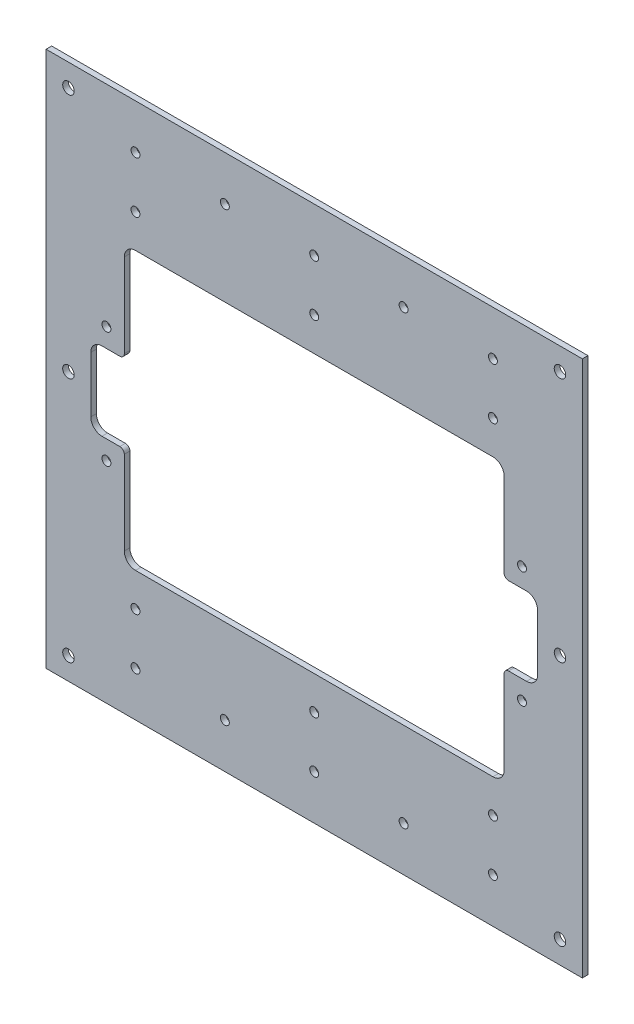
SolidWorks part; units mm, degrees
ref_plane "Front Plane" through (0, 0, 0) normal (0, 0, 1) x (1, 0, 0)
ref_plane "Top Plane" through (0, 0, 0) normal (0, 1, 0) x (1, 0, 0)
ref_plane "Right Plane" through (0, 0, 0) normal (1, 0, 0) x (0, 0, -1)
sketch "Sketch1" plane through (0, 0, 0) normal (0, 0, 1) x (1, 0, 0)
  line L0 (-152.4, 127) -> (-76.2, 127) construction
  line L1 (-152.4, 152.4) -> (152.4, 152.4)
  line L2 (-152.4, 152.4) -> (-152.4, -152.4)
  line L3 (-152.4, -152.4) -> (152.4, -152.4)
  line L4 (152.4, 152.4) -> (152.4, -152.4)
  line L5 (-76.2, 127) -> (-25.4, 127) construction
  line L6 (-25.4, 127) -> (25.4, 127) construction
  line L7 (25.4, 127) -> (76.2, 127) construction
  line L8 (76.2, 127) -> (152.4, 127) construction
  line L9 (-152.4, 0) -> (152.4, 0) construction
  line L10 (0, 152.4) -> (0, -152.4) construction
  line L11 (-118.11, 152.4) -> (-118.11, -152.4) construction
  line L12 (-152.4, -127) -> (152.4, -127) construction
  line L13 (127, 152.4) -> (127, -152.4) construction
  line L14 (-50.8, 152.4) -> (-50.8, -152.4) construction
  line L15 (50.8, 152.4) -> (50.8, -152.4) construction
  line L16 (-101.6, 152.4) -> (-101.6, -152.4) construction
  line L17 (-95.25, 66.04) -> (-57.15, 66.04) construction
  line L18 (-95.25, 66.04) -> (-95.25, -66.04) construction
  line L19 (-95.25, -66.04) -> (-57.15, -66.04) construction
  line L20 (-57.15, 66.04) -> (-57.15, -66.04) construction
  line L21 (-44.45, 66.04) -> (-6.35, 66.04) construction
  line L22 (-44.45, 66.04) -> (-44.45, -66.04) construction
  line L23 (-44.45, -66.04) -> (-6.35, -66.04) construction
  line L24 (-6.35, 66.04) -> (-6.35, -66.04) construction
  line L25 (6.35, 66.04) -> (44.45, 66.04) construction
  line L26 (6.35, 66.04) -> (6.35, -66.04) construction
  line L27 (6.35, -66.04) -> (44.45, -66.04) construction
  line L28 (44.45, 66.04) -> (44.45, -66.04) construction
  line L29 (57.15, 66.04) -> (95.25, 66.04) construction
  line L30 (57.15, 66.04) -> (57.15, -66.04) construction
  line L31 (57.15, -66.04) -> (95.25, -66.04) construction
  line L32 (95.25, 66.04) -> (95.25, -66.04) construction
  line L33 (101.6, 152.4) -> (101.6, -152.4) construction
  line L34 (-152.4, 120.65) -> (152.4, 120.65) construction
  line L35 (-101.6, 39.7057) -> (-95.25, 39.7057) construction
  line L36 (-57.15, 39.7057) -> (-50.8, 39.7057) construction
  line L37 (-76.2, 66.04) -> (-76.2, 0) construction
  line L38 (-76.2, 0) -> (-76.2, -66.04) construction
  line L39 (-152.4, 72.39) -> (152.4, 72.39) construction
  line L40 (-152.4, -72.39) -> (152.4, -72.39) construction
  line L41 (-76.2, 66.04) -> (-76.2, 72.39) construction
  line L42 (-95.25, -66.04) -> (-95.25, -72.39) construction
  line L43 (95.25, 39.7057) -> (101.6, 39.7057) construction
  line L44 (-95.25, 111.76) -> (-57.15, 111.76) construction
  line L45 (-57.15, 111.76) -> (-57.15, 118.4779) construction
  line L46 (-94.0266, 120.65) -> (-78.1749, 130.2582) construction
  line L47 (-95.25, 111.76) -> (-95.25, 118.4779) construction
  line L48 (-58.3734, 120.65) -> (-74.2251, 130.2582) construction
  line L49 (-107.3169, 130.81) -> (-83.1894, 130.81) construction
  line L50 (-6.35, 111.76) -> (-6.35, 118.4779) construction
  line L51 (-7.5734, 120.65) -> (-23.4251, 130.2582) construction
  line L52 (-43.2266, 120.65) -> (-27.3749, 130.2582) construction
  line L53 (-44.45, 111.76) -> (-44.45, 118.4779) construction
  line L54 (-6.35, 111.76) -> (-44.45, 111.76) construction
  line L55 (44.45, 111.76) -> (44.45, 118.4779) construction
  line L56 (43.2266, 120.65) -> (27.3749, 130.2582) construction
  line L57 (7.5734, 120.65) -> (23.4251, 130.2582) construction
  line L58 (6.35, 111.76) -> (6.35, 118.4779) construction
  line L59 (6.35, 111.76) -> (44.45, 111.76) construction
  line L60 (95.25, 111.76) -> (57.15, 111.76) construction
  line L61 (95.25, 111.76) -> (95.25, 118.4779) construction
  line L62 (94.0266, 120.65) -> (78.1749, 130.2582) construction
  line L63 (58.3734, 120.65) -> (74.2251, 130.2582) construction
  line L64 (57.15, 111.76) -> (57.15, 118.4779) construction
  line L65 (-95.25, -111.76) -> (-95.25, -118.4779) construction
  line L66 (-94.0266, -120.65) -> (-78.1749, -130.2582) construction
  line L67 (-58.3734, -120.65) -> (-74.2251, -130.2582) construction
  line L68 (-95.25, -111.76) -> (-57.15, -111.76) construction
  line L69 (-57.15, -111.76) -> (-57.15, -118.4779) construction
  line L70 (-44.45, -111.76) -> (-44.45, -118.4779) construction
  line L71 (-43.2266, -120.65) -> (-27.3749, -130.2582) construction
  line L72 (-6.35, -111.76) -> (-44.45, -111.76) construction
  line L73 (-7.5734, -120.65) -> (-23.4251, -130.2582) construction
  line L74 (-6.35, -111.76) -> (-6.35, -118.4779) construction
  line L75 (6.35, -111.76) -> (6.35, -118.4779) construction
  line L76 (7.5734, -120.65) -> (23.4251, -130.2582) construction
  line L77 (43.2266, -120.65) -> (27.3749, -130.2582) construction
  line L78 (6.35, -111.76) -> (44.45, -111.76) construction
  line L79 (44.45, -111.76) -> (44.45, -118.4779) construction
  line L80 (57.15, -111.76) -> (57.15, -118.4779) construction
  line L81 (58.3734, -120.65) -> (74.2251, -130.2582) construction
  line L82 (94.0266, -120.65) -> (78.1749, -130.2582) construction
  line L83 (95.25, -111.76) -> (57.15, -111.76) construction
  line L84 (95.25, -111.76) -> (95.25, -118.4779) construction
  line L85 (-152.4, 97.79) -> (152.4, 97.79) construction
  line L86 (-50.8, 39.7057) -> (-44.45, 39.7057) construction
  line L87 (-127, 152.4) -> (-127, -152.4) construction
  line L89 (-95.25, 101.6) -> (-92.3192, 101.6) construction
  line L90 (-95.25, 101.6) -> (-95.25, -101.6) construction
  line L96 (-90.8538, 101.6) -> (-90.8538, 68.58) construction
  line L97 (-89.3885, 101.6) -> (-89.3885, 68.58) construction
  line L98 (-92.3192, 101.6) -> (-92.3192, 68.58) construction
  line L99 (-83.5269, 101.6) -> (-83.5269, 68.58) construction
  line L100 (-86.4577, 101.6) -> (-86.4577, 68.58) construction
  line L101 (-89.3885, 101.6) -> (-86.4577, 101.6) construction
  line L102 (-77.6654, 101.6) -> (-77.6654, 68.58) construction
  line L103 (-80.5962, 101.6) -> (-80.5962, 68.58) construction
  line L104 (-83.5269, 101.6) -> (-80.5962, 101.6) construction
  line L105 (-71.8038, 101.6) -> (-71.8038, 68.58) construction
  line L106 (-74.7346, 101.6) -> (-74.7346, 68.58) construction
  line L107 (-77.6654, 101.6) -> (-74.7346, 101.6) construction
  line L108 (-65.9423, 101.6) -> (-65.9423, 68.58) construction
  line L109 (-68.8731, 101.6) -> (-68.8731, 68.58) construction
  line L110 (-71.8038, 101.6) -> (-68.8731, 101.6) construction
  line L111 (-60.0808, 101.6) -> (-60.0808, 68.58) construction
  line L112 (-63.0115, 101.6) -> (-63.0115, 68.58) construction
  line L113 (-65.9423, 101.6) -> (-63.0115, 101.6) construction
  line L114 (-57.15, -101.6) -> (-57.15, 101.6) construction
  line L115 (-60.0808, 101.6) -> (-57.15, 101.6) construction
  line L116 (-92.3192, 68.58) -> (-89.3885, 68.58) construction
  line L117 (-60.0808, -101.6) -> (-57.15, -101.6) construction
  line L118 (-60.0808, -101.6) -> (-60.0808, -68.58) construction
  line L119 (-63.0115, -101.6) -> (-63.0115, -68.58) construction
  line L120 (-65.9423, -101.6) -> (-65.9423, -68.58) construction
  line L121 (-65.9423, -101.6) -> (-63.0115, -101.6) construction
  line L122 (-68.8731, -101.6) -> (-68.8731, -68.58) construction
  line L123 (-71.8038, -101.6) -> (-68.8731, -101.6) construction
  line L124 (-71.8038, -101.6) -> (-71.8038, -68.58) construction
  line L125 (-74.7346, -101.6) -> (-74.7346, -68.58) construction
  line L126 (-77.6654, -101.6) -> (-74.7346, -101.6) construction
  line L127 (-77.6654, -101.6) -> (-77.6654, -68.58) construction
  line L128 (-80.5962, -101.6) -> (-80.5962, -68.58) construction
  line L129 (-83.5269, -101.6) -> (-80.5962, -101.6) construction
  line L130 (-83.5269, -101.6) -> (-83.5269, -68.58) construction
  line L131 (-86.4577, -101.6) -> (-86.4577, -68.58) construction
  line L132 (-89.3885, -101.6) -> (-86.4577, -101.6) construction
  line L133 (-89.3885, -101.6) -> (-89.3885, -68.58) construction
  line L134 (-92.3192, -101.6) -> (-92.3192, -68.58) construction
  line L135 (-95.25, -101.6) -> (-92.3192, -101.6) construction
  line L136 (-9.2808, 68.58) -> (-12.2115, 68.58) construction
  line L137 (6.35, 66.04) -> (44.45, 66.04) construction
  line L138 (-6.35, -66.04) -> (-6.35, -72.39) construction
  line L139 (-25.4, 66.04) -> (-25.4, 72.39) construction
  line L140 (-25.4, 0) -> (-25.4, -66.04) construction
  line L141 (-25.4, 66.04) -> (-25.4, 0) construction
  line L142 (-44.45, 66.04) -> (-44.45, -66.04) construction
  line L143 (-6.35, -66.04) -> (-44.45, -66.04) construction
  line L144 (-6.35, 66.04) -> (-6.35, -66.04) construction
  line L145 (-6.35, 66.04) -> (-44.45, 66.04) construction
  line L146 (-6.35, -101.6) -> (-9.2808, -101.6) construction
  line L147 (-9.2808, -101.6) -> (-9.2808, -68.58) construction
  line L148 (-12.2115, -101.6) -> (-12.2115, -68.58) construction
  line L149 (-12.2115, -101.6) -> (-15.1423, -101.6) construction
  line L150 (-15.1423, -101.6) -> (-15.1423, -68.58) construction
  line L151 (-18.0731, -101.6) -> (-18.0731, -68.58) construction
  line L152 (-18.0731, -101.6) -> (-21.0038, -101.6) construction
  line L153 (-21.0038, -101.6) -> (-21.0038, -68.58) construction
  line L154 (-23.9346, -101.6) -> (-23.9346, -68.58) construction
  line L155 (-23.9346, -101.6) -> (-26.8654, -101.6) construction
  line L156 (-26.8654, -101.6) -> (-26.8654, -68.58) construction
  line L157 (-29.7962, -101.6) -> (-29.7962, -68.58) construction
  line L158 (-29.7962, -101.6) -> (-32.7269, -101.6) construction
  line L159 (-32.7269, -101.6) -> (-32.7269, -68.58) construction
  line L160 (-35.6577, -101.6) -> (-38.5885, -101.6) construction
  line L161 (-35.6577, -101.6) -> (-35.6577, -68.58) construction
  line L162 (-38.5885, -101.6) -> (-38.5885, -68.58) construction
  line L163 (-41.5192, -101.6) -> (-41.5192, -68.58) construction
  line L164 (-41.5192, -101.6) -> (-44.45, -101.6) construction
  line L165 (-41.5192, 101.6) -> (-44.45, 101.6) construction
  line L166 (-44.45, -101.6) -> (-44.45, 101.6) construction
  line L167 (-35.6577, 101.6) -> (-38.5885, 101.6) construction
  line L168 (-38.5885, 101.6) -> (-38.5885, 68.58) construction
  line L169 (-41.5192, 101.6) -> (-41.5192, 68.58) construction
  line L170 (-29.7962, 101.6) -> (-32.7269, 101.6) construction
  line L171 (-32.7269, 101.6) -> (-32.7269, 68.58) construction
  line L172 (-35.6577, 101.6) -> (-35.6577, 68.58) construction
  line L173 (-23.9346, 101.6) -> (-26.8654, 101.6) construction
  line L174 (-26.8654, 101.6) -> (-26.8654, 68.58) construction
  line L175 (-29.7962, 101.6) -> (-29.7962, 68.58) construction
  line L176 (-18.0731, 101.6) -> (-21.0038, 101.6) construction
  line L177 (-21.0038, 101.6) -> (-21.0038, 68.58) construction
  line L178 (-23.9346, 101.6) -> (-23.9346, 68.58) construction
  line L179 (-12.2115, 101.6) -> (-15.1423, 101.6) construction
  line L180 (-15.1423, 101.6) -> (-15.1423, 68.58) construction
  line L181 (-18.0731, 101.6) -> (-18.0731, 68.58) construction
  line L182 (-9.2808, 101.6) -> (-9.2808, 68.58) construction
  line L183 (-12.2115, 101.6) -> (-12.2115, 68.58) construction
  line L184 (-6.35, 101.6) -> (-6.35, -101.6) construction
  line L185 (-6.35, 101.6) -> (-9.2808, 101.6) construction
  line L186 (6.35, 66.04) -> (6.35, -66.04) construction
  line L187 (6.35, -66.04) -> (44.45, -66.04) construction
  line L188 (44.45, 66.04) -> (44.45, -66.04) construction
  line L189 (25.4, 66.04) -> (25.4, 0) construction
  line L190 (25.4, 0) -> (25.4, -66.04) construction
  line L191 (25.4, 66.04) -> (25.4, 72.39) construction
  line L192 (6.35, -66.04) -> (6.35, -72.39) construction
  line L193 (9.2808, 68.58) -> (12.2115, 68.58) construction
  line L194 (6.35, 66.04) -> (6.35, -66.04) construction
  line L195 (44.45, -66.04) -> (6.35, -66.04) construction
  line L196 (44.45, 66.04) -> (44.45, -66.04) construction
  line L197 (44.45, 66.04) -> (6.35, 66.04) construction
  line L198 (6.35, 101.6) -> (9.2808, 101.6) construction
  line L199 (6.35, 101.6) -> (6.35, -101.6) construction
  line L200 (12.2115, 101.6) -> (12.2115, 68.58) construction
  line L201 (9.2808, 101.6) -> (9.2808, 68.58) construction
  line L202 (18.0731, 101.6) -> (18.0731, 68.58) construction
  line L203 (15.1423, 101.6) -> (15.1423, 68.58) construction
  line L204 (12.2115, 101.6) -> (15.1423, 101.6) construction
  line L205 (23.9346, 101.6) -> (23.9346, 68.58) construction
  line L206 (21.0038, 101.6) -> (21.0038, 68.58) construction
  line L207 (18.0731, 101.6) -> (21.0038, 101.6) construction
  line L208 (29.7962, 101.6) -> (29.7962, 68.58) construction
  line L209 (26.8654, 101.6) -> (26.8654, 68.58) construction
  line L210 (23.9346, 101.6) -> (26.8654, 101.6) construction
  line L211 (35.6577, 101.6) -> (35.6577, 68.58) construction
  line L212 (32.7269, 101.6) -> (32.7269, 68.58) construction
  line L213 (29.7962, 101.6) -> (32.7269, 101.6) construction
  line L214 (41.5192, 101.6) -> (41.5192, 68.58) construction
  line L215 (38.5885, 101.6) -> (38.5885, 68.58) construction
  line L216 (35.6577, 101.6) -> (38.5885, 101.6) construction
  line L217 (44.45, -101.6) -> (44.45, 101.6) construction
  line L218 (41.5192, 101.6) -> (44.45, 101.6) construction
  line L219 (41.5192, -101.6) -> (44.45, -101.6) construction
  line L220 (41.5192, -101.6) -> (41.5192, -68.58) construction
  line L221 (38.5885, -101.6) -> (38.5885, -68.58) construction
  line L222 (35.6577, -101.6) -> (35.6577, -68.58) construction
  line L223 (35.6577, -101.6) -> (38.5885, -101.6) construction
  line L224 (32.7269, -101.6) -> (32.7269, -68.58) construction
  line L225 (29.7962, -101.6) -> (32.7269, -101.6) construction
  line L226 (29.7962, -101.6) -> (29.7962, -68.58) construction
  line L227 (26.8654, -101.6) -> (26.8654, -68.58) construction
  line L228 (23.9346, -101.6) -> (26.8654, -101.6) construction
  line L229 (23.9346, -101.6) -> (23.9346, -68.58) construction
  line L230 (21.0038, -101.6) -> (21.0038, -68.58) construction
  line L231 (18.0731, -101.6) -> (21.0038, -101.6) construction
  line L232 (18.0731, -101.6) -> (18.0731, -68.58) construction
  line L233 (15.1423, -101.6) -> (15.1423, -68.58) construction
  line L234 (12.2115, -101.6) -> (15.1423, -101.6) construction
  line L235 (12.2115, -101.6) -> (12.2115, -68.58) construction
  line L236 (9.2808, -101.6) -> (9.2808, -68.58) construction
  line L237 (6.35, -101.6) -> (9.2808, -101.6) construction
  line L238 (57.15, 66.04) -> (95.25, 66.04) construction
  line L239 (57.15, 66.04) -> (57.15, -66.04) construction
  line L240 (57.15, -66.04) -> (95.25, -66.04) construction
  line L241 (95.25, 66.04) -> (95.25, -66.04) construction
  line L242 (92.3192, 68.58) -> (89.3885, 68.58) construction
  line L243 (95.25, -66.04) -> (95.25, -72.39) construction
  line L244 (76.2, 66.04) -> (76.2, 72.39) construction
  line L245 (76.2, 0) -> (76.2, -66.04) construction
  line L246 (76.2, 66.04) -> (76.2, 0) construction
  line L247 (57.15, 66.04) -> (57.15, -66.04) construction
  line L248 (95.25, -66.04) -> (57.15, -66.04) construction
  line L249 (95.25, 66.04) -> (95.25, -66.04) construction
  line L250 (95.25, 66.04) -> (57.15, 66.04) construction
  line L251 (57.15, 66.04) -> (57.15, -66.04) construction
  line L252 (95.25, -66.04) -> (57.15, -66.04) construction
  line L253 (95.25, 66.04) -> (95.25, -66.04) construction
  line L254 (95.25, 66.04) -> (57.15, 66.04) construction
  line L255 (95.25, -101.6) -> (92.3192, -101.6) construction
  line L256 (92.3192, -101.6) -> (92.3192, -68.58) construction
  line L257 (89.3885, -101.6) -> (89.3885, -68.58) construction
  line L258 (89.3885, -101.6) -> (86.4577, -101.6) construction
  line L259 (86.4577, -101.6) -> (86.4577, -68.58) construction
  line L260 (83.5269, -101.6) -> (83.5269, -68.58) construction
  line L261 (83.5269, -101.6) -> (80.5962, -101.6) construction
  line L262 (80.5962, -101.6) -> (80.5962, -68.58) construction
  line L263 (77.6654, -101.6) -> (77.6654, -68.58) construction
  line L264 (77.6654, -101.6) -> (74.7346, -101.6) construction
  line L265 (74.7346, -101.6) -> (74.7346, -68.58) construction
  line L266 (71.8038, -101.6) -> (71.8038, -68.58) construction
  line L267 (71.8038, -101.6) -> (68.8731, -101.6) construction
  line L268 (68.8731, -101.6) -> (68.8731, -68.58) construction
  line L269 (65.9423, -101.6) -> (63.0115, -101.6) construction
  line L270 (65.9423, -101.6) -> (65.9423, -68.58) construction
  line L271 (63.0115, -101.6) -> (63.0115, -68.58) construction
  line L272 (60.0808, -101.6) -> (60.0808, -68.58) construction
  line L273 (60.0808, -101.6) -> (57.15, -101.6) construction
  line L274 (60.0808, 101.6) -> (57.15, 101.6) construction
  line L275 (57.15, -101.6) -> (57.15, 101.6) construction
  line L276 (65.9423, 101.6) -> (63.0115, 101.6) construction
  line L277 (63.0115, 101.6) -> (63.0115, 68.58) construction
  line L278 (60.0808, 101.6) -> (60.0808, 68.58) construction
  line L279 (71.8038, 101.6) -> (68.8731, 101.6) construction
  line L280 (68.8731, 101.6) -> (68.8731, 68.58) construction
  line L281 (65.9423, 101.6) -> (65.9423, 68.58) construction
  line L282 (77.6654, 101.6) -> (74.7346, 101.6) construction
  line L283 (74.7346, 101.6) -> (74.7346, 68.58) construction
  line L284 (71.8038, 101.6) -> (71.8038, 68.58) construction
  line L285 (83.5269, 101.6) -> (80.5962, 101.6) construction
  line L286 (80.5962, 101.6) -> (80.5962, 68.58) construction
  line L287 (77.6654, 101.6) -> (77.6654, 68.58) construction
  line L288 (89.3885, 101.6) -> (86.4577, 101.6) construction
  line L289 (86.4577, 101.6) -> (86.4577, 68.58) construction
  line L290 (83.5269, 101.6) -> (83.5269, 68.58) construction
  line L291 (92.3192, 101.6) -> (92.3192, 68.58) construction
  line L292 (89.3885, 101.6) -> (89.3885, 68.58) construction
  line L293 (95.25, 101.6) -> (95.25, -101.6) construction
  line L294 (95.25, 101.6) -> (92.3192, 101.6) construction
  line L295 (-101.6, 39.7057) -> (-107.95, 39.7057) construction
  line L296 (-101.6, 78.74) -> (101.6, 78.74)
  line L298 (-101.6, -78.74) -> (101.6, -78.74)
  line L300 (-97.0611, 78.74) -> (-97.0611, 72.39) construction
  line L301 (-110.49, 22.225) -> (-120.65, 22.225)
  line L302 (-127, 15.875) -> (-127, -15.875)
  line L303 (-120.65, -22.225) -> (-110.49, -22.225)
  line L304 (-90.964, 120.65) -> (-61.436, 120.65) construction
  line L305 (-90.964, 122.2375) -> (-61.436, 122.2375) construction
  line L306 (-90.964, 119.0625) -> (-61.436, 119.0625) construction
  line L307 (-10.636, 120.65) -> (-40.164, 120.65) construction
  line L308 (-10.636, 122.2375) -> (-40.164, 122.2375) construction
  line L309 (-10.636, 119.0625) -> (-40.164, 119.0625) construction
  line L310 (10.636, 120.65) -> (40.164, 120.65) construction
  line L311 (10.636, 122.2375) -> (40.164, 122.2375) construction
  line L312 (10.636, 119.0625) -> (40.164, 119.0625) construction
  line L313 (90.964, 120.65) -> (61.436, 120.65) construction
  line L314 (90.964, 122.2375) -> (61.436, 122.2375) construction
  line L315 (90.964, 119.0625) -> (61.436, 119.0625) construction
  line L316 (90.964, -120.65) -> (61.436, -120.65) construction
  line L317 (90.964, -122.2375) -> (61.436, -122.2375) construction
  line L318 (90.964, -119.0625) -> (61.436, -119.0625) construction
  line L319 (10.636, -120.65) -> (40.164, -120.65) construction
  line L320 (10.636, -122.2375) -> (40.164, -122.2375) construction
  line L321 (10.636, -119.0625) -> (40.164, -119.0625) construction
  line L322 (-10.636, -120.65) -> (-40.164, -120.65) construction
  line L323 (-10.636, -122.2375) -> (-40.164, -122.2375) construction
  line L324 (-10.636, -119.0625) -> (-40.164, -119.0625) construction
  line L325 (-90.964, -120.65) -> (-61.436, -120.65) construction
  line L326 (-90.964, -122.2375) -> (-61.436, -122.2375) construction
  line L327 (-90.964, -119.0625) -> (-61.436, -119.0625) construction
  line L328 (-6.35, 111.125) -> (-6.35, 92.075) construction
  line L329 (-95.25, 111.125) -> (-57.15, 111.125) construction
  line L330 (-95.25, 111.125) -> (-95.25, 92.075) construction
  line L331 (-95.25, 92.075) -> (-57.15, 92.075) construction
  line L332 (-57.15, 111.125) -> (-57.15, 92.075) construction
  line L333 (-6.35, 111.125) -> (-44.45, 111.125) construction
  line L334 (-44.45, 111.125) -> (-44.45, 92.075) construction
  line L335 (-6.35, 92.075) -> (-44.45, 92.075) construction
  line L336 (95.25, 92.075) -> (57.15, 92.075) construction
  line L337 (95.25, 111.125) -> (95.25, 92.075)
  line L338 (95.25, 111.125) -> (57.15, 111.125) construction
  line L339 (57.15, 111.125) -> (57.15, 92.075) construction
  line L340 (44.45, 111.125) -> (44.45, 92.075) construction
  line L341 (6.35, 92.075) -> (44.45, 92.075) construction
  line L342 (6.35, 111.125) -> (44.45, 111.125) construction
  line L343 (6.35, 111.125) -> (6.35, 92.075) construction
  line L344 (-95.25, -92.075) -> (-57.15, -92.075) construction
  line L345 (-95.25, -111.125) -> (-95.25, -92.075) construction
  line L346 (-95.25, -111.125) -> (-57.15, -111.125) construction
  line L347 (-57.15, -111.125) -> (-57.15, -92.075) construction
  line L348 (-44.45, -111.125) -> (-44.45, -92.075) construction
  line L349 (-6.35, -92.075) -> (-44.45, -92.075) construction
  line L350 (-6.35, -111.125) -> (-44.45, -111.125) construction
  line L351 (-6.35, -111.125) -> (-6.35, -92.075) construction
  line L352 (6.35, -111.125) -> (6.35, -92.075) construction
  line L353 (6.35, -92.075) -> (44.45, -92.075) construction
  line L354 (6.35, -111.125) -> (44.45, -111.125) construction
  line L355 (44.45, -111.125) -> (44.45, -92.075) construction
  line L356 (57.15, -111.125) -> (57.15, -92.075) construction
  line L357 (95.25, -111.125) -> (57.15, -111.125) construction
  line L358 (95.25, -111.125) -> (95.25, -92.075) construction
  line L359 (95.25, -92.075) -> (57.15, -92.075) construction
  line L360 (-107.95, 72.39) -> (-107.95, 24.765)
  line L361 (-107.95, 22.225) -> (-107.95, -22.225) construction
  line L362 (-107.95, -24.765) -> (-107.95, -72.39)
  line L363 (3.659, 78.74) -> (3.659, -78.74) construction
  line L364 (120.65, -22.225) -> (110.49, -22.225)
  line L365 (127, 15.875) -> (127, -15.875)
  line L366 (110.49, 22.225) -> (120.65, 22.225)
  line L367 (107.95, 72.39) -> (107.95, 24.765)
  line L368 (107.95, -24.765) -> (107.95, -72.39)
  circle A0 centre (-76.2, 127) radius 2.5527 construction
  circle A1 centre (-25.4, 127) radius 2.5527 construction
  circle A2 centre (25.4, 127) radius 2.5527 construction
  circle A3 centre (76.2, 127) radius 2.5527 construction
  circle A4 centre (-101.6, 0) radius 2.54 construction
  circle A5 centre (-50.8, 0) radius 2.54 construction
  circle A6 centre (0, 0) radius 2.54 construction
  circle A7 centre (101.6, 0) radius 2.54 construction
  circle A8 centre (50.8, 0) radius 2.54 construction
  circle A9 centre (-50.8, 127) radius 2.54
  circle A10 centre (0, 127) radius 2.54
  circle A11 centre (50.8, 127) radius 2.54
  circle A12 centre (-101.6, 72.39) radius 2.54 construction
  circle A13 centre (0, 72.39) radius 2.54 construction
  circle A14 centre (101.6, 72.39) radius 2.54 construction
  circle A15 centre (-101.6, -72.39) radius 2.54 construction
  circle A16 centre (0, -72.39) radius 2.54 construction
  circle A17 centre (101.6, -72.39) radius 2.54 construction
  arc A18 (-74.2251, 130.2582) -> (-78.1749, 130.2582) centre (-76.2, 127) ccw construction
  arc A19 (-57.15, 118.4779) -> (-58.3734, 120.65) centre (-59.69, 118.4779) ccw construction
  arc A20 (-95.25, 118.4779) -> (-94.0266, 120.65) centre (-92.71, 118.4779) cw construction
  arc A21 (-6.35, 118.4779) -> (-7.5734, 120.65) centre (-8.89, 118.4779) ccw construction
  arc A22 (-27.3749, 130.2582) -> (-23.4251, 130.2582) centre (-25.4, 127) cw construction
  arc A23 (-44.45, 118.4779) -> (-43.2266, 120.65) centre (-41.91, 118.4779) cw construction
  arc A24 (44.45, 118.4779) -> (43.2266, 120.65) centre (41.91, 118.4779) ccw construction
  arc A25 (27.3749, 130.2582) -> (23.4251, 130.2582) centre (25.4, 127) ccw construction
  arc A26 (6.35, 118.4779) -> (7.5734, 120.65) centre (8.89, 118.4779) cw construction
  arc A27 (95.25, 118.4779) -> (94.0266, 120.65) centre (92.71, 118.4779) ccw construction
  arc A28 (74.2251, 130.2582) -> (78.1749, 130.2582) centre (76.2, 127) cw construction
  arc A29 (57.15, 118.4779) -> (58.3734, 120.65) centre (59.69, 118.4779) cw construction
  circle A30 centre (-76.2, -127) radius 2.5527 construction
  circle A31 centre (-25.4, -127) radius 2.5527 construction
  circle A32 centre (25.4, -127) radius 2.5527 construction
  circle A33 centre (76.2, -127) radius 2.5527 construction
  arc A34 (-95.25, -118.4779) -> (-94.0266, -120.65) centre (-92.71, -118.4779) ccw construction
  arc A35 (-74.2251, -130.2582) -> (-78.1749, -130.2582) centre (-76.2, -127) cw construction
  arc A36 (-57.15, -118.4779) -> (-58.3734, -120.65) centre (-59.69, -118.4779) cw construction
  arc A37 (-44.45, -118.4779) -> (-43.2266, -120.65) centre (-41.91, -118.4779) ccw construction
  arc A38 (-27.3749, -130.2582) -> (-23.4251, -130.2582) centre (-25.4, -127) ccw construction
  arc A39 (-6.35, -118.4779) -> (-7.5734, -120.65) centre (-8.89, -118.4779) cw construction
  arc A40 (6.35, -118.4779) -> (7.5734, -120.65) centre (8.89, -118.4779) ccw construction
  arc A41 (27.3749, -130.2582) -> (23.4251, -130.2582) centre (25.4, -127) cw construction
  arc A42 (44.45, -118.4779) -> (43.2266, -120.65) centre (41.91, -118.4779) cw construction
  arc A43 (57.15, -118.4779) -> (58.3734, -120.65) centre (59.69, -118.4779) ccw construction
  arc A44 (74.2251, -130.2582) -> (78.1749, -130.2582) centre (76.2, -127) ccw construction
  arc A45 (95.25, -118.4779) -> (94.0266, -120.65) centre (92.71, -118.4779) cw construction
  circle A46 centre (50.8, -127) radius 2.54
  circle A47 centre (0, -127) radius 2.54
  circle A48 centre (-50.8, -127) radius 2.54
  circle A49 centre (-101.6, 97.79) radius 2.54
  circle A50 centre (0, 97.79) radius 2.54
  circle A51 centre (101.6, 97.79) radius 2.54
  circle A52 centre (101.6, 127) radius 2.54
  circle A53 centre (-101.6, 127) radius 2.54
  circle A54 centre (-118.11, 33.02) radius 2.54
  circle A56 centre (-101.6, -127) radius 2.54
  circle A57 centre (101.6, -127) radius 2.54
  circle A58 centre (101.6, -97.79) radius 2.54
  circle A59 centre (0, -97.79) radius 2.54
  circle A60 centre (-101.6, -97.79) radius 2.54
  circle A61 centre (-118.11, -33.02) radius 2.54
  circle A63 centre (-139.7, 139.7) radius 3.2639
  circle A64 centre (-139.7, 0) radius 3.2639
  circle A65 centre (-139.7, -139.7) radius 3.2639
  circle A66 centre (139.7, -139.7) radius 3.2639
  circle A67 centre (139.7, 0) radius 3.2639
  circle A68 centre (139.7, 139.7) radius 3.2639
  arc A70 (-92.3192, 68.58) -> (-89.3885, 68.58) centre (-90.8538, 68.58) ccw construction
  arc A71 (-86.4577, 68.58) -> (-83.5269, 68.58) centre (-84.9923, 68.58) ccw construction
  arc A72 (-80.5962, 68.58) -> (-77.6654, 68.58) centre (-79.1308, 68.58) ccw construction
  arc A73 (-74.7346, 68.58) -> (-71.8038, 68.58) centre (-73.2692, 68.58) ccw construction
  arc A74 (-68.8731, 68.58) -> (-65.9423, 68.58) centre (-67.4077, 68.58) ccw construction
  arc A75 (-63.0115, 68.58) -> (-60.0808, 68.58) centre (-61.5462, 68.58) ccw construction
  arc A76 (-63.0115, -68.58) -> (-60.0808, -68.58) centre (-61.5462, -68.58) cw construction
  arc A77 (-68.8731, -68.58) -> (-65.9423, -68.58) centre (-67.4077, -68.58) cw construction
  arc A78 (-74.7346, -68.58) -> (-71.8038, -68.58) centre (-73.2692, -68.58) cw construction
  arc A79 (-80.5962, -68.58) -> (-77.6654, -68.58) centre (-79.1308, -68.58) cw construction
  arc A80 (-86.4577, -68.58) -> (-83.5269, -68.58) centre (-84.9923, -68.58) cw construction
  arc A81 (-92.3192, -68.58) -> (-89.3885, -68.58) centre (-90.8538, -68.58) cw construction
  arc A82 (-9.2808, -68.58) -> (-12.2115, -68.58) centre (-10.7462, -68.58) ccw construction
  arc A83 (-15.1423, -68.58) -> (-18.0731, -68.58) centre (-16.6077, -68.58) ccw construction
  arc A84 (-21.0038, -68.58) -> (-23.9346, -68.58) centre (-22.4692, -68.58) ccw construction
  arc A85 (-26.8654, -68.58) -> (-29.7962, -68.58) centre (-28.3308, -68.58) ccw construction
  arc A86 (-32.7269, -68.58) -> (-35.6577, -68.58) centre (-34.1923, -68.58) ccw construction
  arc A87 (-38.5885, -68.58) -> (-41.5192, -68.58) centre (-40.0538, -68.58) ccw construction
  arc A88 (-38.5885, 68.58) -> (-41.5192, 68.58) centre (-40.0538, 68.58) cw construction
  arc A89 (-32.7269, 68.58) -> (-35.6577, 68.58) centre (-34.1923, 68.58) cw construction
  arc A90 (-26.8654, 68.58) -> (-29.7962, 68.58) centre (-28.3308, 68.58) cw construction
  arc A91 (-21.0038, 68.58) -> (-23.9346, 68.58) centre (-22.4692, 68.58) cw construction
  arc A92 (-15.1423, 68.58) -> (-18.0731, 68.58) centre (-16.6077, 68.58) cw construction
  arc A93 (-9.2808, 68.58) -> (-12.2115, 68.58) centre (-10.7462, 68.58) cw construction
  arc A94 (9.2808, 68.58) -> (12.2115, 68.58) centre (10.7462, 68.58) ccw construction
  arc A95 (15.1423, 68.58) -> (18.0731, 68.58) centre (16.6077, 68.58) ccw construction
  arc A96 (21.0038, 68.58) -> (23.9346, 68.58) centre (22.4692, 68.58) ccw construction
  arc A97 (26.8654, 68.58) -> (29.7962, 68.58) centre (28.3308, 68.58) ccw construction
  arc A98 (32.7269, 68.58) -> (35.6577, 68.58) centre (34.1923, 68.58) ccw construction
  arc A99 (38.5885, 68.58) -> (41.5192, 68.58) centre (40.0538, 68.58) ccw construction
  arc A100 (38.5885, -68.58) -> (41.5192, -68.58) centre (40.0538, -68.58) cw construction
  arc A101 (32.7269, -68.58) -> (35.6577, -68.58) centre (34.1923, -68.58) cw construction
  arc A102 (26.8654, -68.58) -> (29.7962, -68.58) centre (28.3308, -68.58) cw construction
  arc A103 (21.0038, -68.58) -> (23.9346, -68.58) centre (22.4692, -68.58) cw construction
  arc A104 (15.1423, -68.58) -> (18.0731, -68.58) centre (16.6077, -68.58) cw construction
  arc A105 (9.2808, -68.58) -> (12.2115, -68.58) centre (10.7462, -68.58) cw construction
  arc A106 (92.3192, -68.58) -> (89.3885, -68.58) centre (90.8538, -68.58) ccw construction
  arc A107 (86.4577, -68.58) -> (83.5269, -68.58) centre (84.9923, -68.58) ccw construction
  arc A108 (80.5962, -68.58) -> (77.6654, -68.58) centre (79.1308, -68.58) ccw construction
  arc A109 (74.7346, -68.58) -> (71.8038, -68.58) centre (73.2692, -68.58) ccw construction
  arc A110 (68.8731, -68.58) -> (65.9423, -68.58) centre (67.4077, -68.58) ccw construction
  arc A111 (63.0115, -68.58) -> (60.0808, -68.58) centre (61.5462, -68.58) ccw construction
  arc A112 (63.0115, 68.58) -> (60.0808, 68.58) centre (61.5462, 68.58) cw construction
  arc A113 (68.8731, 68.58) -> (65.9423, 68.58) centre (67.4077, 68.58) cw construction
  arc A114 (74.7346, 68.58) -> (71.8038, 68.58) centre (73.2692, 68.58) cw construction
  arc A115 (80.5962, 68.58) -> (77.6654, 68.58) centre (79.1308, 68.58) cw construction
  arc A116 (86.4577, 68.58) -> (83.5269, 68.58) centre (84.9923, 68.58) cw construction
  arc A117 (92.3192, 68.58) -> (89.3885, 68.58) centre (90.8538, 68.58) cw construction
  arc A118 (-101.6, 78.74) -> (-107.95, 72.39) centre (-101.6, 72.39) ccw
  arc A119 (-107.95, -72.39) -> (-101.6, -78.74) centre (-101.6, -72.39) ccw
  arc A120 (101.6, 78.74) -> (107.95, 72.39) centre (101.6, 72.39) cw
  arc A121 (101.6, -78.74) -> (107.95, -72.39) centre (101.6, -72.39) ccw
  arc A122 (-127, -15.875) -> (-120.65, -22.225) centre (-120.65, -15.875) ccw
  arc A123 (-120.65, 22.225) -> (-127, 15.875) centre (-120.65, 15.875) ccw
  arc A124 (-90.964, 122.2375) -> (-90.964, 119.0625) centre (-90.964, 120.65) ccw construction
  arc A125 (-61.436, 119.0625) -> (-61.436, 122.2375) centre (-61.436, 120.65) ccw construction
  arc A126 (-10.636, 122.2375) -> (-10.636, 119.0625) centre (-10.636, 120.65) cw construction
  arc A127 (-40.164, 119.0625) -> (-40.164, 122.2375) centre (-40.164, 120.65) cw construction
  arc A128 (10.636, 122.2375) -> (10.636, 119.0625) centre (10.636, 120.65) ccw construction
  arc A129 (40.164, 119.0625) -> (40.164, 122.2375) centre (40.164, 120.65) ccw construction
  arc A130 (90.964, 122.2375) -> (90.964, 119.0625) centre (90.964, 120.65) cw construction
  arc A131 (61.436, 119.0625) -> (61.436, 122.2375) centre (61.436, 120.65) cw construction
  arc A132 (90.964, -122.2375) -> (90.964, -119.0625) centre (90.964, -120.65) ccw construction
  arc A133 (61.436, -119.0625) -> (61.436, -122.2375) centre (61.436, -120.65) ccw construction
  arc A134 (10.636, -122.2375) -> (10.636, -119.0625) centre (10.636, -120.65) cw construction
  arc A135 (40.164, -119.0625) -> (40.164, -122.2375) centre (40.164, -120.65) cw construction
  arc A136 (-10.636, -122.2375) -> (-10.636, -119.0625) centre (-10.636, -120.65) ccw construction
  arc A137 (-40.164, -119.0625) -> (-40.164, -122.2375) centre (-40.164, -120.65) ccw construction
  arc A138 (-90.964, -122.2375) -> (-90.964, -119.0625) centre (-90.964, -120.65) cw construction
  arc A139 (-61.436, -119.0625) -> (-61.436, -122.2375) centre (-61.436, -120.65) cw construction
  arc A140 (-110.49, -22.225) -> (-107.95, -24.765) centre (-110.49, -24.765) cw
  arc A141 (-110.49, 22.225) -> (-107.95, 24.765) centre (-110.49, 24.765) ccw
  arc A142 (110.49, -22.225) -> (107.95, -24.765) centre (110.49, -24.765) ccw
  arc A143 (127, -15.875) -> (120.65, -22.225) centre (120.65, -15.875) cw
  arc A144 (120.65, 22.225) -> (127, 15.875) centre (120.65, 15.875) cw
  arc A145 (110.49, 22.225) -> (107.95, 24.765) centre (110.49, 24.765) cw
  circle A146 centre (118.11, -33.02) radius 2.54
  circle A147 centre (118.11, 33.02) radius 2.54
  point P10 (-76.2, 111.76)
  point P63 (50.8, 127)
  point P95 (-76.2, 66.04)
  point P97 (-25.4, 66.04)
  point P99 (25.4, 66.04)
  point P101 (76.2, 66.04)
  point P116 (-95.25, 0)
  point P118 (-44.45, 0)
  point P119 (6.35, 0)
  point P120 (57.15, 0)
  point P219 (-76.2, 33.02)
  point P259 (0, 78.74)
  point P260 (3.659, 0)
  point P545 (-127, 0)
  point P548 (-127, -22.225)
  point P551 (-127, 22.225)
  point P554 (-76.2, 120.65)
  point P562 (-25.4, 120.65)
  point P569 (25.4, 120.65)
  point P576 (76.2, 120.65)
  point P583 (76.2, -120.65)
  point P590 (25.4, -120.65)
  point P597 (-25.4, -120.65)
  point P604 (-76.2, -120.65)
  point P612 (-57.15, 101.6)
  point P613 (-58.6154, 101.6)
  dimension "D1" = 5.1054
  dimension "D7" = 5.08
  dimension "D11" = 7.62
  dimension "D13" = 2.54
  dimension "D19" = 6.5278
  dimension "D25" = 6.35
  dimension "D26" = 6.35
  dimension "D27" = 6.35
  dimension "D29" = 6.35
  dimension "D32" = 2.54
  dimension "D2" = 25.4
  dimension "D3" = 50.8
  dimension "D4" = 25.4
  dimension "D5" = 25.4
  dimension "D6" = 25.4
  dimension "D8" = 38.1
  dimension "D9" = 31.75
  dimension "D10" = 132.08
  dimension "D12" = 19.05
  dimension "D14" = 25.4
  dimension "D15" = 304.8
  dimension "D16" = 304.8
  dimension "D17" = 8.89
  dimension "D18" = 12.7
  dimension "D20" = 12.7
  dimension "D21" = 12.7
  dimension "D23" = 33.02
  dimension "D24" = 10.16
  dimension "D28" = 44.45
  dimension "D30" = 3.175
  dimension "D31" = 19.05
  dimension "D22" = 6
extrude "Boss-Extrude1" add sketch "Sketch1" along normal blind 3.175 contours L4 L1 L2 L3 A67 A147 A60 A58 A56 A146 A54 A53 A52 A51 A50 A49 A47 L84 A45 L82 A44 L81 A43 L80 L83 L74 A39 L73 A38 L71 A37 L70 L72 L64 A29
